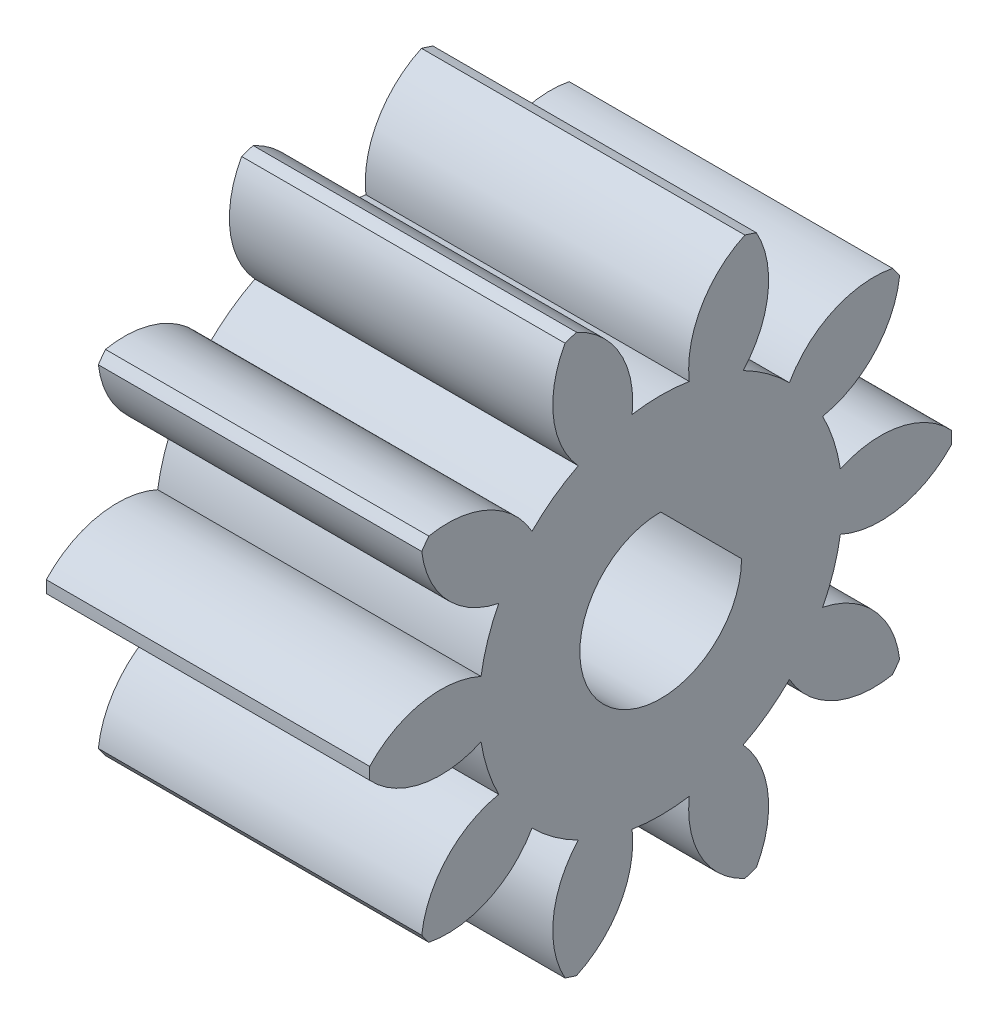
SolidWorks part; units mm, degrees
ref_plane "Plane1" through (0, 0, 0) normal (0, 0, 1) x (1, 0, 0)
ref_plane "Plane2" through (0, 0, 0) normal (0, 1, 0) x (1, 0, 0)
ref_plane "Plane3" through (0, 0, 0) normal (1, 0, 0) x (0, 0, -1)
other "Configuration Table"
sketch "HoldingSke" plane through (0, 0, 0) normal (0, 1, 0) x (1, 0, 0)
  line L0 (0, 0) -> (0.6565, -0.1158)
  line L1 (-15, 0) -> (100, 0) construction
  line L2 (0, 0) -> (-2.1039, 2.3779)
  line L3 (0, 0) -> (-11.863, 4.5341)
  line L4 (0, 0) -> (8.5048, 1.4996)
  line L5 (0, 0) -> (-46.8476, -17.4728)
  line L6 (0, 0) -> (-8.2896, -5.593)
  line L7 (-2.1039, 2.3779) -> (8.6586, 51.2059)
  line L8 (-76.2, 54.61) -> (-75.3, 54.61)
  line L9 (-71.009, 38.7566) -> (-53.1078, 45.2721)
  line L10 (-76.2, 71.12) -> (104.1128, 71.12)
  line L11 (0, 0) -> (-10, 0)
  line L12 (-76.2, 101.6) -> (-76.147, 101.6)
  line L13 (24.9733, 27.94) -> (52.9518, 28.4284)
  line L14 (24.9733, 27.94) -> (24.9743, 27.94)
  line L15 (24.9733, 27.94) -> (100.4006, 29.5858)
  line L16 (-63.627, -1.5) -> (-12.827, -1.5)
  circle A0 centre (0, 0) radius 2.5
  circle A1 centre (0, 0) radius 5.624
  circle A2 centre (0, 0) radius 37.5
  circle A3 centre (0, 0) radius 2.5
  dimension "MHD" = 11.248
  dimension "Hub_dia" = 75
  dimension "Bore" = 5
  dimension "MBD" = 5
  dimension "Num_teeth" = 10
  dimension "Pitch" = 0.6667
  dimension "Overall_len" = 50
  dimension "Show_teeth" = 10
  dimension "Thickness" = 10
  dimension "OAL" = 50.0001
  dimension "T_dim" = 0.9
  dimension "Ap" = 20
  dimension "H" = 19.05
  dimension "Pitch_radius" = 180.3128
  dimension "Width" = 10
  dimension "Backlash" = 0.053
  dimension "Addendum_fac" = 1
  dimension "Dedendum_fac" = 1.25
  dimension "Clearance_fac" = 0.25
  dimension "Dedendum_add" = 0.001
  dimension "Module" = 1.5
sketch "BasProSke" plane through (0, 0, 0) normal (0, 1, 0) x (1, 0, 0)
  line L0 (-10, 0) -> (60, 0) construction
  line L1 (0, 0) -> (0, 9)
  line L2 (0, 0) -> (10, 0)
  line L3 (10, 0) -> (10, 9)
  line L4 (10, 9) -> (0, 9)
  dimension "Thickness" = 10
  dimension "Diameter" = 18
revolve "Base-Revolve" add sketch "BasProSke" angle 360 about L0
sketch "TooCutSke" plane through (0, 0, 0) normal (1, 0, 0) x (0, 0, -1)
  line L1 (0, 0) -> (0, 107) construction
  line L2 (0, 0) -> (-1.2658, 7.3924) construction
  line L3 (0, 0) -> (-4.5869, 14.117) construction
  line L4 (-1.2658, 7.3924) -> (-2.2934, 7.0585) construction
  arc A0 (0.8839, 5.5541) -> (-0.8839, 5.5541) centre (0, 0) ccw
  arc A1 (2.6378, 8.6313) -> (-2.6378, 8.6313) centre (0, 0) ccw
  circle A2 centre (0, 0) radius 7.5 construction
  circle A3 centre (0, 0) radius 7.0477 construction
  arc A4 (-0.8839, 5.5541) -> (-2.6378, 8.6313) centre (-3.8646, 5.8936) ccw
  arc A5 (2.6378, 8.6313) -> (0.8839, 5.5541) centre (3.8646, 5.8936) ccw
  dimension "Root_dia" = 11.248
  dimension "Overcut_dia" = 18.0508
  dimension "Pitch_dia" = 15
  dimension "Base_dia" = 14.0954
  dimension "Flank_rad" = 3
  dimension "Half_ang" = 18
  dimension "Half_CT" = 1.0805
extrude "ToothCut" cut sketch "TooCutSke" along normal through all
fillet "Breaks" [suppressed] radius 0.03
fillet "RootFillets" [suppressed] radius 0.376
pattern_circular "TeethCuts" count 10 every 36 about axis through (-10, 0, 0) along (1, 0, 0) of "ToothCut", "RootFillets", "Breaks"
sketch "HubNeaOneSke" plane through (0, 0, 0) normal (-1, 0, 0) x (0, 0, 1)
  circle A0 centre (0, 0) radius 5.624
  dimension "Diameter" = 11.248
extrude "HubNearOne" [suppressed] add sketch "HubNeaOneSke" along normal blind 40.0001
sketch "HubNeaBotSke" plane through (0, 0, 0) normal (-1, 0, 0) x (0, 0, 1)
  circle A0 centre (0, 0) radius 5.624
  dimension "Diameter" = 11.248
extrude "HubNearBoth" [suppressed] add sketch "HubNeaBotSke" along normal blind 20
ref_plane "FarPln" through (10, 0, 0) normal (1, 0, 0) x (0, 0, -1)
sketch "HubFarSke" plane through (10, 0, 0) normal (1, 0, 0) x (0, 0, -1)
  circle A0 centre (0, 0) radius 5.624
  dimension "Diameter" = 11.248
extrude "HubFar" [suppressed] add sketch "HubFarSke" along normal blind 20
sketch "BorSke" plane through (0, 0, 0) normal (1, 0, 0) x (0, 0, -1)
  circle A0 centre (0, 0) radius 2.5
  dimension "Diameter" = 5
extrude "Bore" cut sketch "BorSke" along normal mid plane 100.0001
sketch "KeySke" plane through (0, 0, 0) normal (1, 0, 0) x (0, 0, -1)
  line L0 (-1, 0) -> (-1, 3.4)
  line L1 (-1, 3.4) -> (1, 3.4)
  line L2 (1, 3.4) -> (1, 0)
  line L3 (0, 0) -> (0, 34) construction
  line L4 (-1, 0) -> (1, 0)
  dimension "Offset" = 3.4
  dimension "Width" = 2
extrude "Keyway" [suppressed] cut sketch "KeySke" along normal mid plane 100.0001
pattern_circular "Keyway2" [suppressed] count 2 every 90 about axis through (-10, 0, 0) along (1, 0, 0)
sketch "Sketch1" plane through (10, 0, 0) normal (1, 0, 0) x (0, 0, -1)
  line L0 (0, 0) -> (0, 2.5) construction
  line L1 (0, 0) -> (2.5, 0) construction
  line L2 (0, 2.5) -> (2.5, 0)
  arc A2 (0, 2.5) -> (2.5, 0) centre (0, 0) cw
  circle A3 centre (0, 0) radius 2.5 construction
  point P5 (2.5, 0.2356)
extrude "Boss-Extrude1" add sketch "Sketch1" against normal through all
equation "' \"Module@HoldingSke\" = 6.35"
equation "' \"Num_teeth@HoldingSke\" = 12"
equation "' \"Ap@HoldingSke\" =  20"
equation "' \"Ap@HoldingSke\" = 20"
equation "' \"Width@HoldingSke\" = 0.5 * 25.4"
equation "' \"Hub_dia@HoldingSke\"= 1 * 25.4"
equation "' \"Hub_dia@HoldingSke\" = 1 * 25.4"
equation "' \"Overall_len@HoldingSke\" = 1.0 * 25.4"
equation "' \"Bore@HoldingSke\" = 0.75 * 25.4"
equation "' \"T_dim@HoldingSke\" = 0.1 * 25.4"
equation "' \"Width@KeySke\" = 0.25 * 25.4"
equation "' \"Show_teeth@HoldingSke\" = 13"
equation "' \"Backlash@HoldingSke\" = 0.009 * 25.4"
equation "' \"Addendum_fac@HoldingSke\" = 1.0"
equation "' \"Dedendum_fac@HoldingSke\" = 1.25"
equation "' \"Dedendum_add@HoldingSke\" = 0.00005 * 25.4"
equation "' \"Clearance_fac@HoldingSke\" = 0.25"
equation "\"Pitch@HoldingSke\" = 1 / \"Module@HoldingSke\""
equation "\"Overcut_dia@TooCutSke\" = (\"Num_teeth@HoldingSke\" + 2 * \"Addendum_fac@HoldingSke\") / \"Pitch@HoldingSke\" + 0.002 * 25.4"
equation "\"Pitch_dia@TooCutSke\" = \"Num_teeth@HoldingSke\" / \"Pitch@HoldingSke\""
equation "\"Base_dia@TooCutSke\" = \"Num_teeth@HoldingSke\" / \"Pitch@HoldingSke\" * cos((\"Ap@HoldingSke\"  * 3.14159265 / 180))"
equation "\"Root_dia@TooCutSke\" = (\"Num_teeth@HoldingSke\" + 2) / \"Pitch@HoldingSke\" - 2 * (\"Addendum_fac@HoldingSke\" + \"Dedendum_fac@HoldingSke\") / \"Pitch@HoldingSke\" - \"Dedendum_add@HoldingSke\" * 2"
equation "\"Half_ang@TooCutSke\" = 180 / \"Num_teeth@HoldingSke\""
equation "\"Half_CT@TooCutSke\" = \"Num_teeth@HoldingSke\" / \"Pitch@HoldingSke\" * sin((3.14159265 / 2 / \"Num_teeth@HoldingSke\")) / 2 - 7 * \"Backlash@HoldingSke\" / 4"
equation "\"Flank_rad@TooCutSke\" = \"Num_teeth@HoldingSke\" / \"Pitch@HoldingSke\" / 5"
equation "\"Radius@RootFillets\" = \"Clearance_fac@HoldingSke\" / \"Pitch@HoldingSke\" + \"Dedendum_add@HoldingSke\""
equation "\"Break_rad@Breaks\" = 0.02 / \"Pitch@HoldingSke\""
equation "\"Thickness@HoldingSke\" = \"Width@HoldingSke\""
equation "\"OAL@HoldingSke\" = \"Thickness@HoldingSke\""
equation "\"MHD@HoldingSke\" = (\"Num_teeth@HoldingSke\" + 2) / \"Pitch@HoldingSke\" - 2 * (\"Addendum_fac@HoldingSke\" + \"Dedendum_fac@HoldingSke\")  / \"Pitch@HoldingSke\" - \"Dedendum_add@HoldingSke\" * 2"
equation "\"MBD@HoldingSke\" = (\"Num_teeth@HoldingSke\" + 2) / \"Pitch@HoldingSke\" - 2 * (\"Addendum_fac@HoldingSke\" + \"Dedendum_fac@HoldingSke\")  / \"Pitch@HoldingSke\" - \"Dedendum_add@HoldingSke\" * 2 - 0.002 * 25.4"
equation "\"MHD@HoldingSke\" = ((sgn( \"MHD@HoldingSke\" - \"Hub_dia@HoldingSke\" )-1)*( \"MHD@HoldingSke\" - \"Hub_dia@HoldingSke\" ))/-2+ \"Hub_dia@HoldingSke\""
equation "\"MBD@HoldingSke\" = ((sgn( \"MBD@HoldingSke\" - \"Bore@HoldingSke\" )-1)*( \"MBD@HoldingSke\" - \"Bore@HoldingSke\" ))/-2+ \"Bore@HoldingSke\""
equation "\"OAL@HoldingSke\" = ((sgn( \"OAL@HoldingSke\" - \"Overall_len@HoldingSke\" )+1)*( \"OAL@HoldingSke\" - \"Overall_len@HoldingSke\" ))/2 + \"Overall_len@HoldingSke\" + 0.000002 * 25.4"
equation "\"Num_teeth@TeethCuts\" = int( \"Show_teeth@HoldingSke\" ) + 1"
equation "\"Num_teeth@TeethCuts\" = ((sgn( \"Num_teeth@TeethCuts\" - \"Num_teeth@HoldingSke\" )-1)*( \"Num_teeth@TeethCuts\" - \"Num_teeth@HoldingSke\" ))/-2+ \"Num_teeth@HoldingSke\""
equation "\"Num_teeth@TeethCuts\" = ((sgn( \"Num_teeth@TeethCuts\" - 2.0)+1)*( \"Num_teeth@TeethCuts\" - 2.0))/2 +2.0"
equation "\"Angle@TeethCuts\" = 360.0 / \"Num_teeth@HoldingSke\""
equation "\"Diameter@BasProSke\" = (\"Num_teeth@HoldingSke\" + 2 * \"Addendum_fac@HoldingSke\") / \"Pitch@HoldingSke\""
equation "\"Thickness@BasProSke\"  = \"Thickness@HoldingSke\""
equation "' \"Fillet_rad@BasProSke\" =  \"Thickness@HoldingSke\" * 0.05"
equation "' \"Fillet_rad@BasProSke\" = \"Thickness@HoldingSke\" * 0.05"
equation "\"MHD@HoldingSke\" = ((sgn( \"MHD@HoldingSke\" - \"Root_dia@TooCutSke\" )-1)*( \"MHD@HoldingSke\" - \"Root_dia@TooCutSke\" ))/-2+ \"Root_dia@TooCutSke\""
equation "\"Diameter@HubNeaOneSke\" = \"MHD@HoldingSke\""
equation "\"Length@HubNearOne\" = \"OAL@HoldingSke\" - \"Thickness@BasProSke\""
equation "\"Diameter@HubNeaBotSke\" = \"MHD@HoldingSke\""
equation "\"Length@HubNearBoth\" = ( \"OAL@HoldingSke\" - \"Thickness@BasProSke\" ) / 2.0"
equation "\"Thickness@FarPln\" = \"Thickness@BasProSke\""
equation "\"Diameter@HubFarSke\" = \"MHD@HoldingSke\""
equation "\"Length@HubFar\" = ( \"OAL@HoldingSke\" - \"Thickness@BasProSke\" ) / 2.0"
equation "\"Diameter@BorSke\" = \"MBD@HoldingSke\""
equation "\"D1@Bore\" = \"OAL@HoldingSke\" * 2.0"
equation "\"D1@Keyway\" = \"OAL@HoldingSke\" * 2.0"
equation "\"Offset@KeySke\" = \"T_dim@HoldingSke\" + \"MBD@HoldingSke\" / 2.0"
